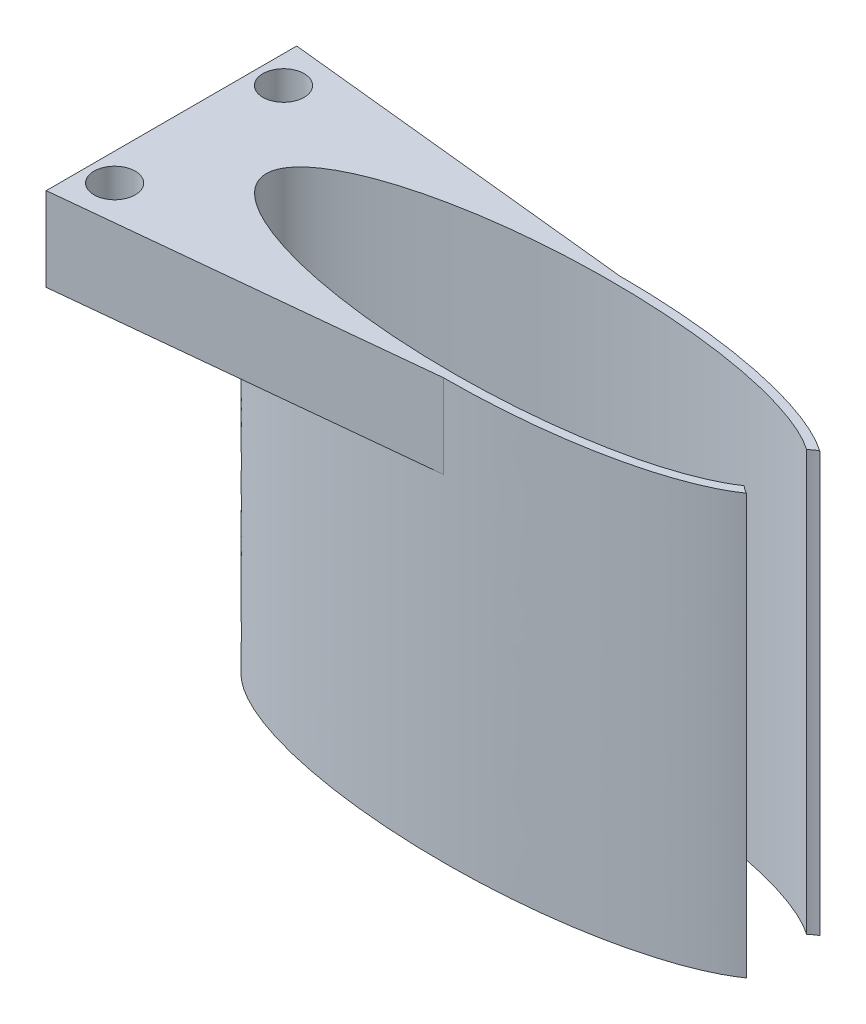
SolidWorks part; units mm, degrees
ref_plane "Front Plane" through (0, 0, 0) normal (0, 0, 1) x (1, 0, 0)
ref_plane "Top Plane" through (0, 0, 0) normal (0, 1, 0) x (1, 0, 0)
ref_plane "Right Plane" through (0, 0, 0) normal (1, 0, 0) x (0, 0, -1)
sketch "Sketch1" plane through (0, 0, 0) normal (0, 1, 0) x (1, 0, 0)
  ellipse E0 centre (0, 0) end of major axis (83.8671, 0) minor radius 26.7152
  ellipse E1 centre (0, 0) end of major axis (80.4114, 0) minor radius 24.057
extrude "Boss-Extrude1" add sketch "Sketch1" along normal blind 127.254
sketch "Sketch2" plane through (0, 127.254, 0) normal (0, 1, 0) x (1, 0, 0)
  circle A0 centre (82.3628, 0) radius 12.6959
extrude "Cut-Extrude1" cut sketch "Sketch2" against normal blind 157.48
sketch "Sketch4" plane through (0, 127.254, 0) normal (0, 1, 0) x (1, 0, 0)
  line L1 (-109.2888, 26.7152) -> (-109.2888, -26.7152)
  line L3 (-109.2888, 26.7152) -> (-109.2888, 38.1203)
  line L4 (-109.2888, -26.7152) -> (-109.2888, -37.8054)
  line L5 (0, -26.7152) -> (-109.2888, -37.8054)
  line L6 (0, 26.7152) -> (-109.2888, 38.1203)
  arc A2 (76.2477, 11.1261) -> (73.9122, 9.4748) centre (82.3628, 0) ccw
  arc A3 (73.9122, -9.4748) -> (76.2477, -11.1261) centre (82.3628, 0) ccw
  ellipse E1 centre (0, 0) end of major axis (83.8671, 0) minor radius 26.7152 (76.2477, 11.1261) -> (76.2477, -11.1261) ccw construction
  ellipse E4 centre (0, 0) end of major axis (83.8671, 0) minor radius 26.7152 (76.2477, 11.1261) -> (76.2477, -11.1261) ccw
  ellipse E5 centre (0, 0) end of major axis (80.4114, 0) minor radius 24.057 (73.9122, 9.4748) -> (73.9122, -9.4748) ccw
  ellipse E6 centre (0, 0) end of major axis (83.8671, 0) minor radius 26.7152 (0, 26.7152) -> (0, -26.7152) ccw
  dimension "D1" = 0
extrude "Boss-Extrude2" add sketch "Sketch4" against normal blind 25.4
sketch "Sketch5" plane through (0, 127.254, 0) normal (0, 1, 0) x (1, 0, 0)
  line L0 (-100.9234, 37.2473) -> (-100.9234, 25.753)
  line L1 (0, 26.7152) -> (-109.2888, 38.1203) construction
  line L2 (-100.9234, -36.9565) -> (-100.9234, -25.438)
  line L3 (-109.2888, -37.8054) -> (0, -26.7152) construction
  circle A0 centre (-100.9234, 25.753) radius 6.2434
  circle A1 centre (-100.9234, -25.438) radius 6.2434
extrude "Cut-Extrude2" cut sketch "Sketch5" against normal blind 148.336
